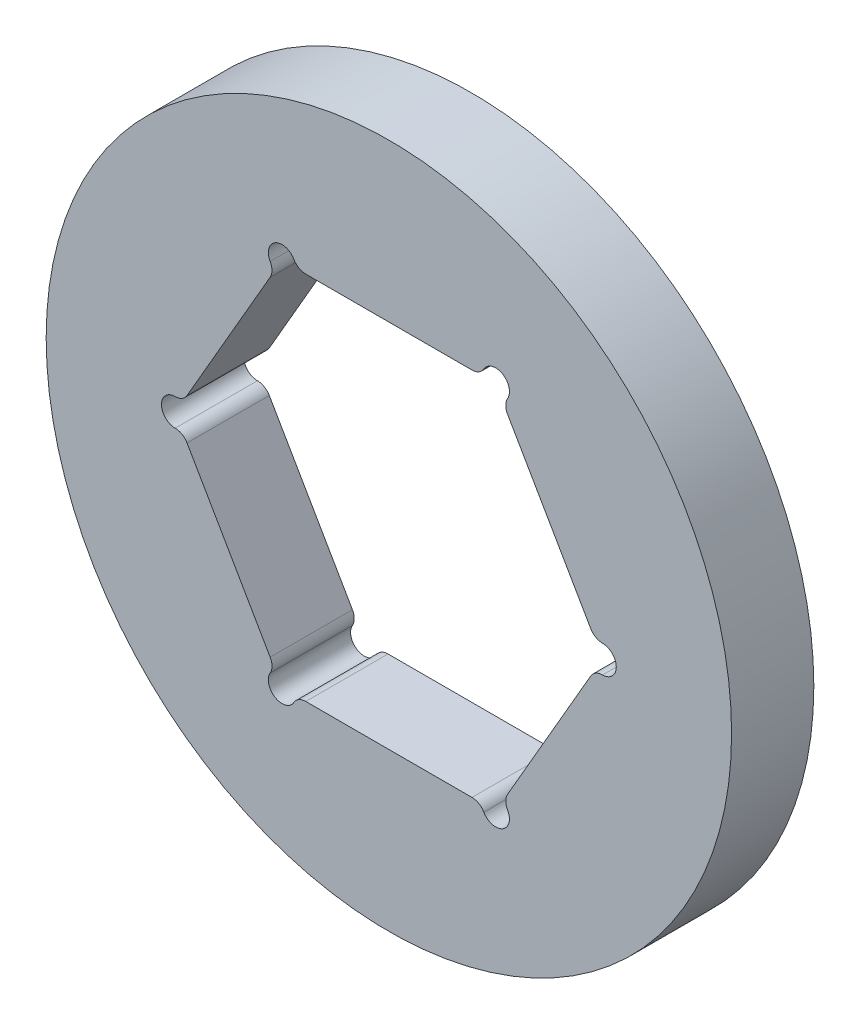
SolidWorks part; units mm, degrees
ref_plane "Front Plane" through (0, 0, 0) normal (0, 0, 1) x (1, 0, 0)
ref_plane "Top Plane" through (0, 0, 0) normal (0, 1, 0) x (1, 0, 0)
ref_plane "Right Plane" through (0, 0, 0) normal (1, 0, 0) x (0, 0, -1)
sketch "Sketch1" plane through (0, 0, 0) normal (0, 0, 1) x (1, 0, 0)
  line L1 (-15.5885, 0) -> (-7.7942, -13.5)
  line L2 (-7.7942, -13.5) -> (7.7942, -13.5)
  line L3 (7.7942, -13.5) -> (15.5885, 0)
  line L4 (15.5885, 0) -> (7.7942, 13.5)
  line L5 (7.7942, 13.5) -> (-7.7942, 13.5)
  line L6 (-7.7942, 13.5) -> (-15.5885, 0)
  circle A0 centre (0, 0) radius 25
  circle A1 centre (0, 0) radius 13.5 construction
  dimension "D1" = 50
  dimension "D2" = 27
extrude "Boss-Extrude1" add sketch "Sketch1" along normal mid plane 6
sketch "Sketch2" plane through (0, 0, 3) normal (0, 0, 1) x (1, 0, 0)
  circle A0 centre (-7.7942, 13.5) radius 1
  circle A1 centre (7.7942, 13.5) radius 1
  circle A2 centre (-15.5885, 0) radius 1
  circle A3 centre (-7.7942, -13.5) radius 1
  circle A4 centre (7.7942, -13.5) radius 1
  circle A5 centre (15.5885, 0) radius 1
  dimension "D1" = 2
extrude "Cut-Extrude1" cut sketch "Sketch2" against normal through all
fillet "Fillet1" radius 1 12 edges at (-15.0885, 0.866, 0) (-15.0885, -0.866, 0) (-8.2942, -12.634, 0) (-6.7942, -13.5, 0) (6.7942, -13.5, 0) (8.2942, -12.634, 0) (15.0885, 0.866, 0) (15.0885, -0.866, 0) (6.7942, 13.5, 0) (8.2942, 12.634, 0) (-8.2942, 12.634, 0) (-6.7942, 13.5, 0)
